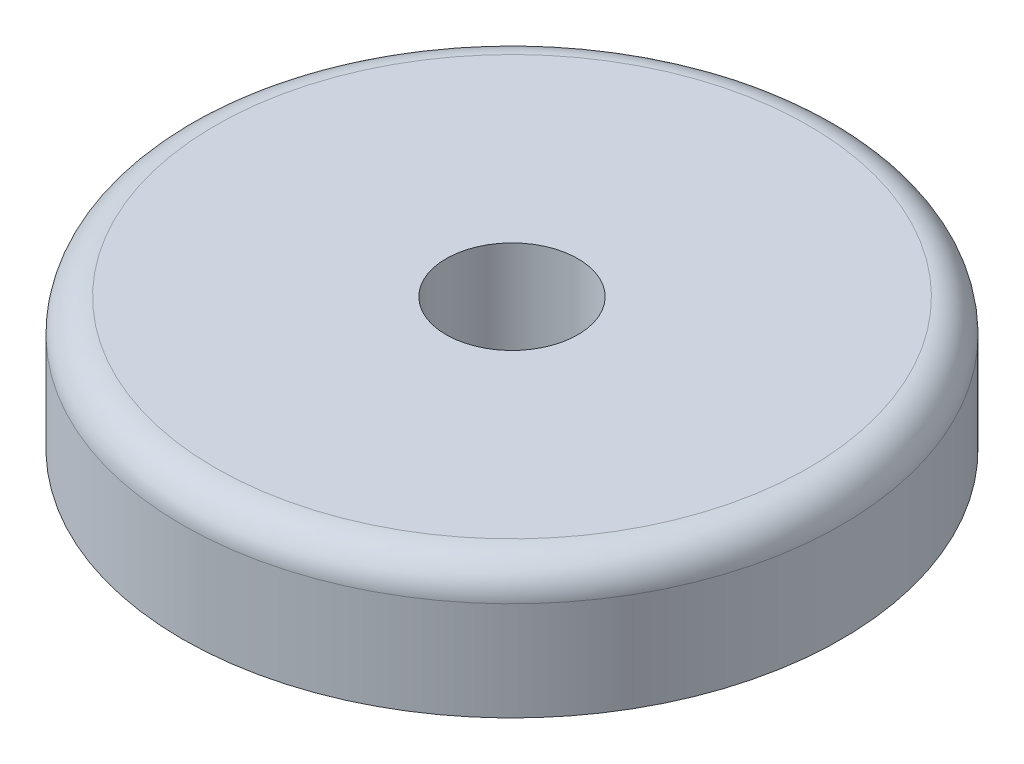
SolidWorks part; units mm, degrees
ref_plane "Front Plane" through (0, 0, 0) normal (0, 0, 1) x (1, 0, 0)
ref_plane "Top Plane" through (0, 0, 0) normal (0, 1, 0) x (1, 0, 0)
ref_plane "Right Plane" through (0, 0, 0) normal (1, 0, 0) x (0, 0, -1)
sketch "Sketch1" plane through (0, 0, 0) normal (0, 1, 0) x (1, 0, 0)
  circle A0 centre (0, 0) radius 5
  dimension "D1" = 10
extrude "Boss-Extrude1" add sketch "Sketch1" along normal blind 2
sketch "Sketch2" plane through (0, 2, 0) normal (0, 1, 0) x (1, 0, 0)
  circle A0 centre (0, 0) radius 1
  dimension "D1" = 2
extrude "Cut-Extrude1" cut sketch "Sketch2" against normal blind 12.5
fillet "Fillet1" radius 0.5 1 edges at (0, 2, 5)
